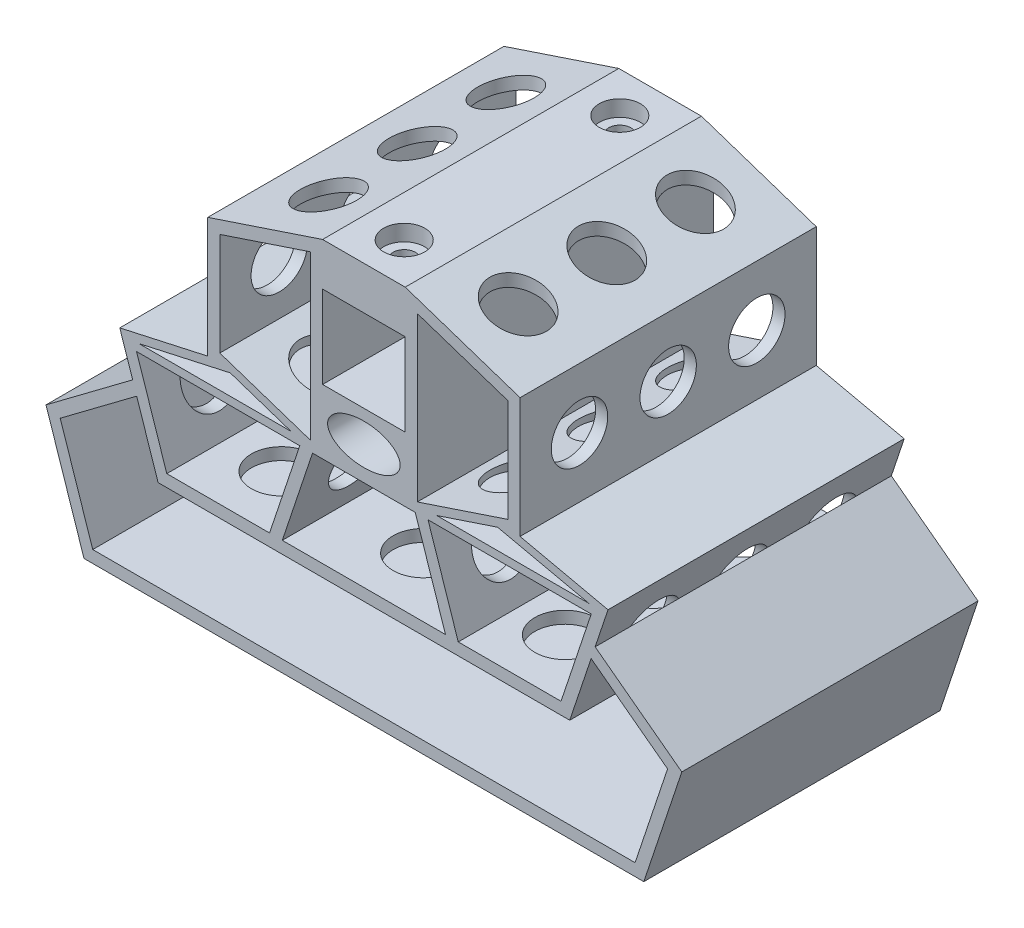
SolidWorks part; units mm, degrees
ref_plane "Front Plane" through (0, 0, 0) normal (0, 0, 1) x (1, 0, 0)
ref_plane "Top Plane" through (0, 0, 0) normal (0, 1, 0) x (1, 0, 0)
ref_plane "Right Plane" through (0, 0, 0) normal (1, 0, 0) x (0, 0, -1)
sketch "Sketch1" plane through (0, 0, 0) normal (0, 0, 1) x (1, 0, 0)
  line L0 (0, 45.5072) -> (0, -40.4348) construction
  line L1 (-48.8406, 0) -> (45.7971, 0) construction
  line L3 (10.25, -10.25) -> (-10.25, -10.25)
  line L4 (10.25, -10.25) -> (10.25, 10.25)
  line L5 (10.25, 10.25) -> (-10.25, 10.25)
  line L6 (-10.25, -10.25) -> (-10.25, 10.25)
  line L7 (10.25, -10.25) -> (-10.25, 10.25) construction
  line L8 (10.25, 10.25) -> (-10.25, -10.25) construction
  line L18 (-12.75, -26.25) -> (12.75, -26.25)
  line L19 (12.75, -26.25) -> (20.25, -48.75)
  line L20 (-20.25, -48.75) -> (20.25, -48.75)
  line L21 (-12.75, -26.25) -> (-20.25, -48.75)
  line L40 (15.9123, -26.25) -> (23.4123, -48.75)
  line L45 (15.9123, -26.25) -> (56.4123, -26.25)
  line L47 (56.4123, -26.25) -> (48.9123, -48.75)
  line L49 (48.9123, -48.75) -> (23.4123, -48.75)
  line L51 (60.5746, -23.25) -> (51.0746, -51.75)
  line L53 (-36.1623, -48.75) -> (-36.1623, -56.6283) construction
  line L54 (15.9123, -23.25) -> (60.5746, -23.25) construction
  line L55 (-15.9123, -26.25) -> (-56.4123, -26.25)
  line L56 (14.9123, -23.25) -> (24.4123, -51.75) construction
  line L57 (-24.4123, -51.75) -> (24.4123, -51.75) construction
  line L58 (51.0746, -51.75) -> (23.4123, -51.75) construction
  line L59 (-56.4123, -26.25) -> (-48.9123, -48.75)
  line L60 (-48.9123, -48.75) -> (-23.4123, -48.75)
  line L61 (-15.9123, -26.25) -> (-23.4123, -48.75)
  line L62 (-14.9123, -23.25) -> (-24.4123, -51.75) construction
  line L64 (-60.5746, -23.25) -> (-51.0746, -51.75)
  line L67 (-11.75, -23.25) -> (-21.25, -51.75) construction
  line L68 (-11.75, -23.25) -> (-60.5746, -23.25) construction
  line L69 (-14.9123, -23.25) -> (14.9123, -23.25) construction
  line L70 (-51.0746, -51.75) -> (-21.25, -51.75) construction
  line L71 (-51.0746, -51.75) -> (51.0746, -51.75)
  line L72 (-13.25, -23.75) -> (-13.25, 16.75)
  line L73 (-13.25, 16.75) -> (-35.75, 9.25)
  line L74 (-35.75, 9.25) -> (-35.75, -16.25)
  line L75 (-35.75, -16.25) -> (-13.25, -23.75)
  line L76 (-39.4516, -3.5) -> (45.7971, -3.5) construction
  line L77 (35.75, 9.25) -> (35.75, -16.25)
  line L78 (13.25, 16.75) -> (35.75, 9.25)
  line L79 (13.25, -23.75) -> (13.25, 16.75)
  line L80 (35.75, -16.25) -> (13.25, -23.75)
  line L83 (-10.25, 20.9123) -> (-38.75, 11.4123)
  line L84 (-38.75, 11.4123) -> (-38.75, -18.4123)
  line L85 (-10.25, -27.9123) -> (-10.25, 20.9123) construction
  line L86 (-38.75, -18.4123) -> (-10.25, -27.9123) construction
  line L87 (-60.5746, -23.25) -> (-38.75, -18.4123)
  line L88 (-10.25, 20.9123) -> (0, 20.9123)
  line L89 (38.75, 11.4123) -> (38.75, -18.4123)
  line L92 (10.25, 20.9123) -> (38.75, 11.4123)
  line L93 (10.25, -27.9123) -> (10.25, 20.9123) construction
  line L94 (38.75, -18.4123) -> (10.25, -27.9123) construction
  line L95 (60.5746, -23.25) -> (38.75, -18.4123)
  line L96 (10.25, 20.9123) -> (0, 20.9123)
  point P5 (0, 0)
  point P10 (0, 0)
  point P13 (0, 14)
  point P14 (0, 35)
  point P16 (22.4772, 38)
  point P18 (-22.4772, 38)
  point P19 (0, 35)
  point P20 (-14.7629, 11)
  point P33 (14.7629, 11)
  dimension "D1" = 20.5
  dimension "D2" = 20.5
  dimension "D3" = 25.5
  dimension "D4" = 40.5
  dimension "D5" = 22.5
  dimension "D6" = 3
  dimension "D8" = 16
  dimension "D9" = 20.25
  dimension "D10" = 3
  dimension "D11" = 40.5
  dimension "D7" = 12.75
  dimension "D13" = 3
  dimension "D14" = 40.5
  dimension "D15" = 25.5
  dimension "D16" = 3.5
  dimension "D17" = 12.75
  dimension "D18" = 20.25
  dimension "D19" = 22.5
  dimension "D12" = 3
  dimension "D20" = 3
  dimension "D21" = 3
extrude "Boss-Extrude1" add sketch "Sketch1" along normal blind 73.5
sketch "Sketch2" plane through (0, 0, 0) normal (0, 0, 1) x (1, 0, 0)
  line L5 (0, 26.7053) -> (0, -60.761) construction
  line L16 (-15.9123, -24.25) -> (-56.4123, -24.25)
  line L17 (-18.0746, -24.25) -> (-55.8442, -24.25)
  line L19 (-38.3172, -20.3649) -> (-60.1417, -25.2026)
  line L20 (-33.1596, -19.2216) -> (-55.8442, -24.25)
  line L21 (18.0746, -24.25) -> (55.8442, -24.25)
  line L22 (-36.3825, -18.1474) -> (-13.8825, -25.6474)
  line L23 (-33.1596, -19.2216) -> (-18.0746, -24.25)
  line L24 (33.1596, -19.2216) -> (55.8442, -24.25)
  line L25 (33.1596, -19.2216) -> (18.0746, -24.25)
  dimension "D1" = 2
  dimension "D2" = 2
  dimension "D3" = 2
extrude "Cut-Extrude2" cut sketch "Sketch2" along normal through all
sketch "Sketch3" plane through (0, 0, 0) normal (0, 0, 1) x (1, 0, 0)
  line L0 (0, 24.4574) -> (0, -32.3369) construction
  ellipse E0 centre (0, -18) end of major axis (9, -18) minor radius 5
  dimension "D1" = 18
  dimension "D2" = 9
  dimension "D5" = 5
extrude "Cut-Extrude4" cut sketch "Sketch3" along normal through all
sketch "Sketch4" plane through (0, 0, 0) normal (1, 0, 0) x (0, 0, -1)
  line L0 (-89.3161, -36.52) -> (42.3095, -36.52) construction
  line L1 (-36.75, 29.8449) -> (-36.75, -56.0115) construction
  line L2 (-36.75, -36.52) -> (-58.75, -36.52) construction
  line L3 (-36.75, -36.52) -> (-14.75, -36.52) construction
  line L4 (-36.75, -36.52) -> (-14.75, -36.52) construction
  circle A0 centre (-36.75, -36.52) radius 7
  circle A2 centre (-58.75, -36.52) radius 7
  circle A3 centre (-14.75, -36.52) radius 7
  dimension "D3" = 14
  dimension "D1" = 36.52
  dimension "D2" = 36.75
  dimension "D5" = 22
  dimension "D7" = 22
  dimension "D6" = 2
  dimension "D4" = 2
extrude "Cut-Extrude5" cut sketch "Sketch4" against normal through all both and the other way through all
sketch "Sketch5" plane through (38.75, 0, 0) normal (1, 0, 0) x (0, 0, -1)
  line L0 (-85.8813, -3.5) -> (19.6328, -3.5) construction
  line L1 (-36.75, -3.5) -> (-14.75, -3.5) construction
  line L2 (-36.75, -3.5) -> (-58.75, -3.5) construction
  circle A0 centre (-36.75, -3.5) radius 7
  circle A1 centre (-14.75, -3.5) radius 7
  circle A2 centre (-58.75, -3.5) radius 7
  dimension "D2" = 14
  dimension "D3" = 36.75
  dimension "D1" = 3.5
  dimension "D5" = 22
  dimension "D7" = 22
  dimension "D4" = 2
  dimension "D6" = 2
extrude "Cut-Extrude6" cut sketch "Sketch5" against normal blind 10
sketch "Sketch6" plane through (-38.75, 0, 0) normal (-1, 0, 0) x (0, 0, 1)
  line L0 (-12.5672, -3.5) -> (85.8413, -3.5) construction
  line L1 (36.75, -3.5) -> (58.75, -3.5) construction
  line L2 (36.75, -3.5) -> (14.75, -3.5) construction
  circle A0 centre (36.75, -3.5) radius 7
  circle A1 centre (58.75, -3.5) radius 7
  circle A2 centre (14.75, -3.5) radius 7
  dimension "D2" = 14
  dimension "D3" = 36.75
  dimension "D1" = 3.5
  dimension "D5" = 22
  dimension "D7" = 22
  dimension "D4" = 2
  dimension "D6" = 2
extrude "Cut-Extrude7" cut sketch "Sketch6" against normal blind 10
sketch "Sketch7" plane through (0, -51.75, 0) normal (0, -1, 0) x (1, 0, 0)
  line L0 (0, 77.452) -> (0, -13.4565) construction
  line L1 (0, 36.75) -> (35.16, 36.75) construction
  line L2 (0, 36.75) -> (-35.16, 36.75) construction
  circle A0 centre (0, 36.75) radius 7.5
  circle A1 centre (35.16, 36.75) radius 7.5
  circle A4 centre (-35.16, 36.75) radius 7.5
  circle A5 centre (0, 58.75) radius 7.5 [skipped]
  circle A6 centre (35.16, 58.75) radius 7.5 [skipped]
  circle A7 centre (0, 58.75) radius 7.5
  circle A8 centre (35.16, 58.75) radius 7.5
  circle A9 centre (-35.16, 58.75) radius 7.5
  circle A10 centre (0, 14.75) radius 7.5
  circle A11 centre (35.16, 14.75) radius 7.5
  circle A12 centre (-35.16, 14.75) radius 7.5
  dimension "D1" = 15
  dimension "D2" = 36.75
  dimension "D5" = 35.16
  dimension "D7" = 35.16
  dimension "D3" = 2
  dimension "D4" = 2
  dimension "D6" = 2
  dimension "D8" = 2
  dimension "D9" = 2
extrude "Cut-Extrude8" cut sketch "Sketch7" against normal blind 10
sketch "Sketch8" plane through (0, 0, 0) normal (0, 1, 0) x (1, 0, 0)
  line L0 (0, 9.1455) -> (0, -79.6194) construction
  circle A0 centre (23.52, -36.75) radius 7
  circle A1 centre (23.52, -14.75) radius 7
  circle A2 centre (23.52, -58.75) radius 7
  circle A3 centre (-23.52, -58.75) radius 7
  circle A4 centre (-23.52, -14.75) radius 7
  circle A5 centre (-23.52, -36.75) radius 7
  dimension "D1" = 14
  dimension "D2" = 36.75
  dimension "D3" = 23.52
  dimension "D4" = 2
  dimension "D5" = 2
extrude "Cut-Extrude9" cut sketch "Sketch8" along normal through all and the other way up to surface other way up to face at (-36.9594, -24.25, 36.75)
sketch "Sketch9" plane through (0, 20.9123, 0) normal (0, 1, 0) x (1, 0, 0)
  line L0 (0, 10.7424) -> (0, -82.6878) construction
  line L1 (-69.9781, -36.75) -> (68.9694, -36.75) construction
  circle A0 centre (0, -10) radius 2.75
  circle A1 centre (0, -63.5) radius 2.75
  point P5 (0, -10)
  dimension "D2" = 5.5
  dimension "D1" = 36.75
  dimension "D4" = 26.75
extrude "Cut-Extrude10" cut sketch "Sketch9" against normal blind 15
sketch "Sketch10" plane through (0, 20.9123, 0) normal (0, 1, 0) x (1, 0, 0)
  circle A0 centre (0, -10) radius 5.1
  circle A1 centre (0, -63.5) radius 5.1
  dimension "D1" = 10.2
  dimension "D2" = 10.2
extrude "Cut-Extrude11" cut sketch "Sketch10" against normal blind 4
sketch "Sketch11" plane through (0, 0, 0) normal (0, 0, 1) x (1, 0, 0)
  line L0 (0, 30.5881) -> (0, -94.1151) construction
  line L1 (-67.031, 0) -> (70.2288, 0) construction
  line L3 (-51.0746, -51.75) -> (51.0746, -51.75) construction
  line L4 (74.6904, -63.2766) -> (33.1073, -49.4155) construction
  line L5 (-20.25, -74.25) -> (20.25, -74.25)
  line L6 (69.4539, -77.25) -> (-69.4539, -77.25)
  line L7 (-20.25, -74.25) -> (-67.2916, -74.25)
  line L8 (-67.2916, -74.25) -> (-75.3554, -50.0586)
  line L9 (-60.5746, -23.25) -> (-51.0746, -51.75) construction
  line L10 (-74.6904, -63.2766) -> (-33.1073, -49.4155) construction
  line L11 (-75.3554, -50.0586) -> (-56.3818, -35.8283)
  line L12 (-57.3818, -32.8283) -> (-56.3818, -35.8283)
  line L13 (-69.4539, -77.25) -> (-78.8853, -48.9559)
  line L14 (-78.8853, -48.9559) -> (-57.3818, -32.8283)
  line L15 (-78.8853, -48.9559) -> (-58.1818, -33.4283) construction
  line L16 (-70.1377, -75.1987) -> (-78.8853, -48.9559) construction
  line L17 (78.8853, -48.9559) -> (57.3818, -32.8283)
  line L18 (69.4539, -77.25) -> (78.8853, -48.9559)
  line L19 (57.3818, -32.8283) -> (56.3818, -35.8283)
  line L20 (75.3554, -50.0586) -> (56.3818, -35.8283)
  line L21 (67.2916, -74.25) -> (75.3554, -50.0586)
  line L22 (20.25, -74.25) -> (67.2916, -74.25)
  point P10 (0, -74.25)
  point P22 (0, 0)
  point P23 (0, 0)
  point P24 (-56.7997, -32.2322)
  point P26 (-69.4569, -77.25)
  point P35 (0, -77.25)
  dimension "D1" = 22.5
  dimension "D3" = 20.25
  dimension "D4" = 3
  dimension "D5" = 22.5
  dimension "D6" = 12.75
  dimension "D7" = 25.5
  dimension "D8" = 20.25
  dimension "D9" = 3
extrude "Boss-Extrude2" add sketch "Sketch11" along normal up to surface (73.5 mm away) up to face at (9, -18, 73.5)
